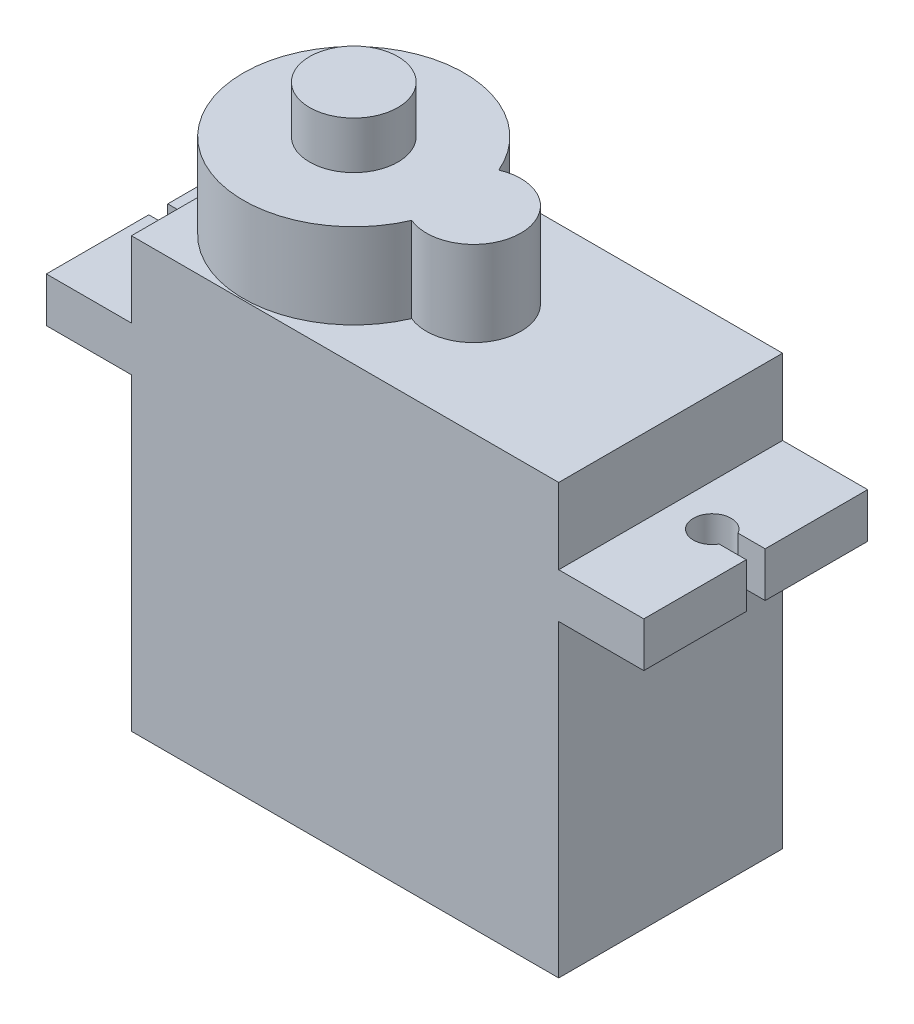
SolidWorks part; units mm, degrees
material "ABS"
ref_plane "Front Plane" through (0, 0, 0) normal (0, 0, 1) x (1, 0, 0)
ref_plane "Top Plane" through (0, 0, 0) normal (0, 1, 0) x (1, 0, 0)
ref_plane "Right Plane" through (0, 0, 0) normal (1, 0, 0) x (0, 0, -1)
sketch "Sketch1" plane through (0, 0, 0) normal (0, 1, 0) x (1, 0, 0)
  line L1 (-46.1955, 4.5831) -> (-23.5955, 4.5831)
  line L2 (-46.1955, 4.5831) -> (-46.1955, -7.2569)
  line L3 (-46.1955, -7.2569) -> (-23.5955, -7.2569)
  line L4 (-23.5955, 4.5831) -> (-23.5955, -7.2569)
  dimension "D1" = 22.6
  dimension "D2" = 11.84
extrude "Boss-Extrude1" add sketch "Sketch1" along normal blind 22.7
ref_plane "Plane1" through (-23.5955, 22.7, -4.5831) normal (0, -1, 0) x (1, 0, 0)
sketch "Sketch2" plane through (-23.5955, 22.7, -4.5831) normal (0, -1, 0) x (1, 0, 0)
ref_plane "Plane2" through (-46.1955, 22.7, -4.5831) normal (0, 0, 1) x (1, 0, 0)
sketch "Sketch3" plane through (-46.1955, 22.7, -4.5831) normal (0, 0, 1) x (1, 0, 0)
sketch "Sketch4" plane through (0, 22.7, 0) normal (0, 1, 0) x (-1, 0, 0)
  line L0 (46.1955, 1.3369) -> (40.3555, 1.3369)
  line L1 (46.1955, -4.5831) -> (46.1955, 7.2569) construction
  circle A0 centre (40.3555, 1.3369) radius 5.84
extrude "Boss-Extrude6" add sketch "Sketch4" along normal blind 4.5
sketch "Sketch12" plane through (0, 27.2, 0) normal (0, 1, 0) x (-1, 0, 0)
  circle A0 centre (40.3555, 1.3369) radius 2.335
extrude "Boss-Extrude7" add sketch "Sketch12" along normal blind 2.5
sketch "Sketch13" plane through (0, 22.7, 0) normal (0, 1, 0) x (-1, 0, 0)
  line L0 (34.5155, 1.3369) -> (34.0155, 1.3369)
  circle A0 centre (40.3555, 1.3369) radius 5.84 construction
  circle A1 centre (34.0155, 1.3369) radius 2.5
extrude "Boss-Extrude8" add sketch "Sketch13" along normal blind 4.5
sketch "Sketch14" plane through (-23.5955, 0, 0) normal (1, 0, 0) x (0, 0, -1)
  line L0 (-7.2569, 22.7) -> (-7.2569, 18.7)
  line L1 (-7.2569, 22.7) -> (-7.2569, 0) construction
  line L2 (4.5831, 22.7) -> (4.5831, 0) construction
  line L3 (-7.2569, 18.7) -> (4.5831, 18.7)
  line L4 (-7.2569, 18.7) -> (-7.2569, 16.33)
  line L5 (-7.2569, 16.33) -> (4.5831, 16.33)
  line L6 (4.5831, 18.7) -> (4.5831, 16.33)
  line M2 (4.5831, 0) -> (4.5831, 22.7)
  line M4 (-7.2569, 22.7) -> (-7.2569, 0)
extrude "Boss-Extrude10" add sketch "Sketch14" along normal blind 4.5 contours L5 L3 M4 M2
sketch "Sketch15" plane through (0, 18.7, 0) normal (0, 1, 0) x (-1, 0, 0)
  line L0 (19.0955, 7.2569) -> (19.0955, -4.5831) construction
  line L1 (19.0955, 1.3369) -> (20.5955, 1.3369)
  line L2 (19.0955, 1.8369) -> (19.0955, 0.8369)
  line L3 (19.0955, 0.8369) -> (20.5955, 0.8369)
  line L4 (50.6955, 1.3369) -> (48.3955, 1.3369)
  line L5 (20.5955, 1.8369) -> (20.5955, 0.8369)
  line L6 (19.0955, 1.8369) -> (20.5955, 1.8369)
  line L7 (19.0955, 1.3369) -> (21.3955, 1.3369)
  circle A0 centre (21.3955, 1.3369) radius 1
  circle A1 centre (48.3955, 1.3369) radius 1
extrude "Cut-Extrude3" cut sketch "Sketch15" along direction (0, 1, 0) on the side against the normal through all
sketch "Sketch16" plane through (-46.1955, 0, 0) normal (-1, 0, 0) x (0, 0, 1)
  line L0 (7.2569, 22.7) -> (7.2569, 18.7)
  line L1 (7.2569, 22.7) -> (7.2569, 0) construction
  line L2 (7.2569, 18.7) -> (7.2569, 16.33)
  line L3 (7.2569, 18.7) -> (-4.5831, 18.7)
  line L4 (-4.5831, 22.7) -> (-4.5831, 0) construction
  line L5 (7.2569, 16.33) -> (-4.5831, 16.33)
  line M2 (7.2569, 0) -> (7.2569, 22.7)
  line M5 (-4.5831, 22.7) -> (-4.5831, 0)
extrude "Boss-Extrude11" add sketch "Sketch16" along normal blind 4.5 contours L5 L3 M2 M5
sketch "Sketch17" plane through (0, 18.7, 0) normal (0, 1, 0) x (-1, 0, 0)
  line L0 (50.6955, 0.8369) -> (50.6955, 1.8369)
  line L1 (50.6955, 1.3369) -> (49.1955, 1.3369)
  line L2 (50.6955, 1.8369) -> (49.1955, 1.8369)
  line L3 (49.1955, 0.8369) -> (49.1955, 1.8369)
  line L4 (50.6955, 7.2569) -> (50.6955, -4.5831) construction
  line L5 (50.6955, 0.8369) -> (49.1955, 0.8369)
  line L6 (50.6955, 1.3369) -> (48.2955, 1.3369)
  circle A0 centre (48.2955, 1.3369) radius 1
extrude "Cut-Extrude4" cut sketch "Sketch17" along direction (0, -1, 0) on the side against the normal through all
sketch "Sketch18" plane through (0, 0, 0) normal (0, -1, 0) x (-1, 0, 0)
  circle A0 centre (40.3555, -1.3369) radius 2.5
  circle A2 centre (40.3555, -1.3369) radius 2.335 construction
  dimension "D1" = 5
extrude "Cut-Extrude5" cut sketch "Sketch18" against normal blind 3
